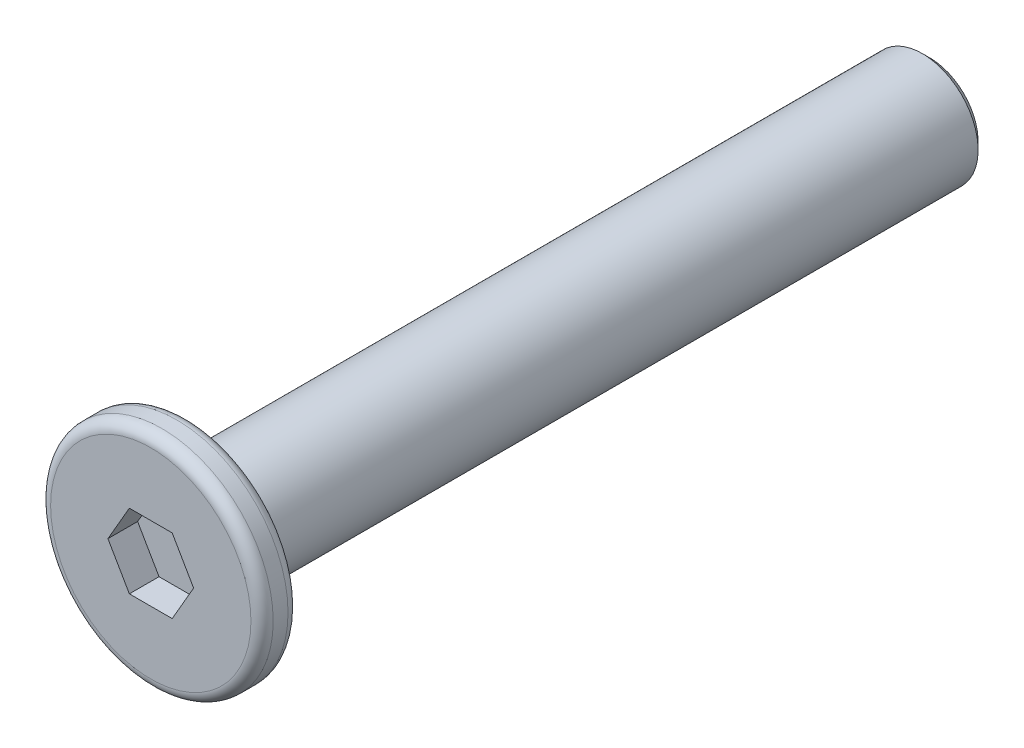
SolidWorks part; units mm, degrees
ref_plane "前视基准面" through (0, 0, 0) normal (0, 0, 1) x (1, 0, 0)
ref_plane "上视基准面" through (0, 0, 0) normal (0, 1, 0) x (1, 0, 0)
ref_plane "右视基准面" through (0, 0, 0) normal (1, 0, 0) x (0, 0, -1)
sketch "草图1" plane through (0, 0, 0) normal (0, 0, 1) x (1, 0, 0)
  circle A0 centre (0, 0) radius 3
  dimension "D1" = 6
extrude "凸台-拉伸1" add sketch "草图1" along normal mid plane 1
sketch "草图2" plane through (0, 0, -0.5) normal (0, 0, -1) x (-1, 0, 0)
  circle A0 centre (0, 0) radius 1.5
  dimension "D1" = 3
extrude "凸台-拉伸2" add sketch "草图2" along normal blind 20
chamfer "倒角1" distance 0.2 angle 45 1 edges at (-1.5, 0, -20.5)
sketch "草图3" plane through (0, 0, 0.5) normal (0, 0, 1) x (1, 0, 0)
  line L1 (1.1547, 0) -> (0.5774, 1)
  line L2 (0.5774, 1) -> (-0.5774, 1)
  line L3 (-0.5774, 1) -> (-1.1547, 0)
  line L4 (-1.1547, 0) -> (-0.5774, -1)
  line L5 (-0.5774, -1) -> (0.5774, -1)
  line L6 (0.5774, -1) -> (1.1547, 0)
  circle A0 centre (0, 0) radius 1 construction
  dimension "D1" = 2
extrude "切除-拉伸1" cut sketch "草图3" against normal blind 0.8
fillet "圆角2" radius 0.3 2 edges at (3, 0, -0.5) (3, 0, 0.5)
